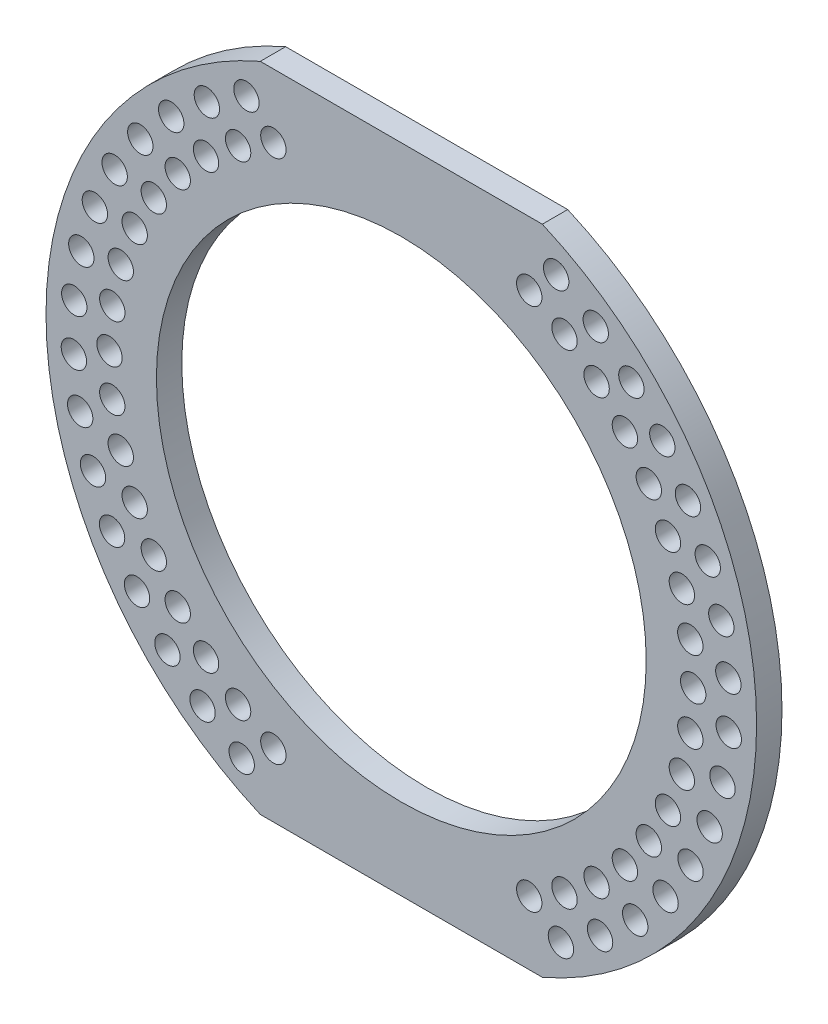
SolidWorks part; units mm, degrees
ref_plane "Ön Düzlem" through (0, 0, 0) normal (0, 0, 1) x (1, 0, 0)
ref_plane "Üst Düzlem" through (0, 0, 0) normal (0, 1, 0) x (1, 0, 0)
ref_plane "Sağ Düzlem" through (0, 0, 0) normal (1, 0, 0) x (0, 0, -1)
sketch "Çizim1" plane through (0, 0, 0) normal (0, 0, 1) x (1, 0, 0)
  line L1 (-11.1135, 25.7) -> (11.1135, 25.7)
  line L3 (-11.1135, -25.7) -> (11.1135, -25.7)
  arc A0 (-11.1135, 25.7) -> (-11.1135, -25.7) centre (0, 0) ccw
  arc A1 (11.1135, -25.7) -> (11.1135, 25.7) centre (0, 0) ccw
  dimension "D1" = 56
  dimension "D2" = 25.7
extrude "Yükseklik-Ekstrüzyon1" add sketch "Çizim1" along normal blind 2
sketch "Çizim2" plane through (0, 0, 2) normal (0, 0, 1) x (1, 0, 0)
  circle A0 centre (0, 0) radius 19.3
  dimension "D1" = 38.6
extrude "Kes-Ekstrüzyon1" cut sketch "Çizim2" against normal blind 3
sketch "Çizim3" plane through (0, 0, 2) normal (0, 0, 1) x (1, 0, 0)
  circle A0 centre (-23, 0) radius 1
  circle A3 centre (-22.7762, 3.201) radius 1
  circle A4 centre (-22.109, 6.3397) radius 1
  circle A5 centre (-21.0115, 9.3549) radius 1
  circle A6 centre (-19.5051, 12.1881) radius 1
  circle A7 centre (-17.619, 14.7841) radius 1
  circle A8 centre (-15.39, 17.0923) radius 1
  circle A9 centre (-12.8614, 19.0679) radius 1
  circle A10 centre (-10.0825, 20.6723) radius 1
  circle A39 centre (-10.0825, -20.6723) radius 1
  circle A40 centre (-12.8614, -19.0679) radius 1
  circle A41 centre (-15.39, -17.0923) radius 1
  circle A42 centre (-17.619, -14.7841) radius 1
  circle A43 centre (-19.5051, -12.1881) radius 1
  circle A44 centre (-21.0115, -9.3549) radius 1
  circle A45 centre (-22.109, -6.3397) radius 1
  circle A46 centre (-22.7762, -3.201) radius 1
  arc A47 (-8.0515, 21.5447) -> (-6.1498, 22.1626) centre (-7.1074, 21.8743) ccw [skipped]
  circle A48 centre (10.0825, -20.6723) radius 1
  arc A49 (-3.0056, 22.8028) -> (-4.9747, 22.4556) centre (-3.9939, 22.6506) ccw [skipped]
  circle A50 centre (12.8614, -19.0679) radius 1
  arc A51 (-1.8011, 22.9294) -> (0.1972, 22.9992) centre (-0.8027, 22.986) ccw [skipped]
  arc A52 (1.4076, 22.9569) -> (3.3962, 22.7479) centre (2.4042, 22.874) ccw [skipped]
  circle A53 centre (15.39, -17.0923) radius 1
  arc A54 (6.529, 22.0538) -> (4.5889, 22.5376) centre (5.5642, 22.3168) ccw [skipped]
  circle A55 centre (17.619, -14.7841) radius 1
  arc A56 (7.6808, 21.6796) -> (9.5348, 20.9306) centre (8.616, 21.3252) ccw [skipped]
  arc A57 (-8.0515, -21.5447) -> (-6.1498, -22.1626) centre (-7.1074, -21.8743) ccw [skipped]
  arc A58 (-3.0056, -22.8028) -> (-4.9747, -22.4556) centre (-3.9939, -22.6506) ccw [skipped]
  arc A59 (12.355, 19.3999) -> (10.6233, 20.3996) centre (11.5, 19.9186) ccw [skipped]
  circle A60 centre (19.5051, -12.1881) radius 1
  arc A61 (19.1774, 12.6975) -> (18.0022, 14.3151) centre (18.6074, 13.5191) ccw [skipped]
  arc A62 (13.359, 18.7226) -> (14.9347, 17.4916) centre (14.1602, 18.1242) ccw [skipped]
  arc A63 (17.2237, 15.2429) -> (15.8347, 16.6812) centre (16.5448, 15.9771) ccw [skipped]
  circle A64 centre (21.0115, -9.3549) radius 1
  arc A65 (20.758, 9.9049) -> (19.8192, 11.6704) centre (20.3078, 10.7978) ccw [skipped]
  arc A66 (21.2506, 8.7985) -> (21.9344, 6.9196) centre (21.6129, 7.8665) ccw [skipped]
  arc A67 (22.2683, 5.7554) -> (22.684, 3.7995) centre (22.4974, 4.782) ccw [skipped]
  arc A68 (22.992, -0.6056) -> (22.8525, -2.6002) centre (22.944, -1.6044) ccw [skipped]
  circle A69 centre (22.944, 1.6044) radius 1 [skipped]
  circle A70 centre (22.109, -6.3397) radius 1
  circle A71 centre (22.4974, -4.782) radius 1 [skipped]
  circle A72 centre (22.7762, -3.201) radius 1
  circle A73 centre (23, 0) radius 1
  arc A74 (15.8347, -16.6812) -> (17.2237, -15.2429) centre (16.5448, -15.9771) ccw [skipped]
  circle A75 centre (22.7762, 3.201) radius 1
  arc A76 (3.3962, -22.7479) -> (1.4076, -22.9569) centre (2.4042, -22.874) ccw [skipped]
  circle A77 centre (22.109, 6.3397) radius 1
  arc A78 (6.529, -22.0538) -> (4.5889, -22.5376) centre (5.5642, -22.3168) ccw [skipped]
  arc A79 (-1.8011, -22.9294) -> (0.1972, -22.9992) centre (-0.8027, -22.986) ccw [skipped]
  circle A80 centre (21.0115, 9.3549) radius 1
  arc A81 (9.5348, -20.9306) -> (7.6808, -21.6796) centre (8.616, -21.3252) ccw [skipped]
  arc A82 (10.6233, -20.3996) -> (12.355, -19.3999) centre (11.5, -19.9186) ccw [skipped]
  arc A83 (21.2506, -8.7985) -> (21.9344, -6.9196) centre (21.6129, -7.8665) ccw [skipped]
  arc A84 (19.1774, -12.6975) -> (18.0022, -14.3151) centre (18.6074, -13.5191) ccw [skipped]
  arc A85 (19.8192, -11.6704) -> (20.758, -9.9049) centre (20.3078, -10.7978) ccw [skipped]
  arc A86 (14.9347, -17.4916) -> (13.359, -18.7226) centre (14.1602, -18.1242) ccw [skipped]
  circle A87 centre (19.5051, 12.1881) radius 1
  circle A88 centre (17.619, 14.7841) radius 1
  circle A89 centre (15.39, 17.0923) radius 1
  circle A90 centre (12.8614, 19.0679) radius 1
  circle A91 centre (10.0825, 20.6723) radius 1
  point P96 (0, 0)
  dimension "D1" = 2
  dimension "D2" = 23
  dimension "D3" = 45
extrude "Kes-Ekstrüzyon2" cut sketch "Çizim3" against normal blind 3
sketch "Çizim4" plane through (0, 0, 2) normal (0, 0, 1) x (1, 0, 0)
  circle A1 centre (-12.2039, 22.7936) radius 1
  circle A30 centre (-12.5773, -22.5897) radius 1
  circle A31 centre (-15.6641, -20.5698) radius 1
  circle A32 centre (-18.4321, -18.1312) radius 1
  circle A33 centre (-20.8248, -15.3235) radius 1
  circle A34 centre (-22.7936, -12.2039) radius 1
  circle A35 centre (-24.2984, -8.8358) radius 1
  circle A36 centre (-25.3085, -5.2878) radius 1
  circle A37 centre (-25.8034, -1.6322) radius 1
  circle A38 centre (-25.7731, 2.0566) radius 1
  circle A39 centre (-25.2181, 5.7036) radius 1
  circle A40 centre (-24.1497, 9.2344) radius 1
  circle A41 centre (-22.5897, 12.5773) radius 1
  circle A42 centre (-20.5698, 15.6641) radius 1
  circle A43 centre (-18.1312, 18.4321) radius 1
  circle A44 centre (-15.3235, 20.8248) radius 1
  circle A45 centre (12.5773, -22.5897) radius 1
  arc A46 (-9.7688, 23.9385) -> (-7.8895, 24.6219) centre (-8.8358, 24.2984) ccw [skipped]
  arc A47 (-10.1614, -23.7745) -> (-8.2936, -24.4887) centre (-9.2344, -24.1497) ccw [skipped]
  arc A48 (-6.6745, -24.9786) -> (-4.7241, -25.4198) centre (-5.7036, -25.2181) ccw [skipped]
  circle A49 centre (15.6641, -20.5698) radius 1
  arc A50 (2.6288, -25.721) -> (0.6332, -25.8473) centre (1.6322, -25.8034) ccw [skipped]
  circle A51 centre (18.4321, -18.1312) radius 1
  arc A52 (6.2625, -25.0851) -> (4.3052, -25.4941) centre (5.2878, -25.3085) ccw [skipped]
  arc A53 (-1.0584, -25.8333) -> (-3.0517, -25.6743) centre (-2.0566, -25.7731) ccw [skipped]
  arc A54 (7.8895, -24.6219) -> (9.7688, -23.9385) centre (8.8358, -24.2984) ccw [skipped]
  circle A55 centre (20.8248, -15.3235) radius 1
  arc A56 (23.0591, -11.6943) -> (22.0864, -13.4414) centre (22.5897, -12.5773) ccw [skipped]
  circle A57 centre (22.7936, -12.2039) radius 1
  arc A58 (11.3133, -23.2485) -> (13.0762, -22.3046) centre (12.2039, -22.7936) ccw [skipped]
  circle A59 centre (18.1312, -18.4321) radius 1 [skipped]
  circle A60 centre (24.2984, -8.8358) radius 1
  arc A61 (16.1173, -20.2167) -> (14.5067, -21.4018) centre (15.3235, -20.8248) ccw [skipped]
  circle A62 centre (25.3085, -5.2878) radius 1
  arc A63 (21.1602, -14.857) -> (19.9487, -16.4478) centre (20.5698, -15.6641) ccw [skipped]
  circle A64 centre (25.8034, -1.6322) radius 1
  arc A65 (25.0851, 6.2625) -> (25.4941, 4.3052) centre (25.3085, 5.2878) ccw [skipped]
  arc A66 (25.6743, -3.0517) -> (25.8333, -1.0584) centre (25.7731, -2.0566) ccw [skipped]
  arc A67 (24.9786, -6.6745) -> (25.4198, -4.7241) centre (25.2181, -5.7036) ccw [skipped]
  arc A68 (24.4887, -8.2936) -> (23.7745, -10.1614) centre (24.1497, -9.2344) ccw [skipped]
  arc A69 (25.721, 2.6288) -> (25.8473, 0.6332) centre (25.8034, 1.6322) ccw [skipped]
  arc A70 (24.6219, 7.8895) -> (23.9385, 9.7688) centre (24.2984, 8.8358) ccw [skipped]
  circle A71 centre (25.7731, 2.0566) radius 1
  arc A72 (20.2167, 16.1173) -> (21.4018, 14.5067) centre (20.8248, 15.3235) ccw [skipped]
  circle A73 centre (25.2181, 5.7036) radius 1
  arc A74 (-6.2625, 25.0851) -> (-4.3052, 25.4941) centre (-5.2878, 25.3085) ccw [skipped]
  circle A75 centre (24.1497, 9.2344) radius 1
  arc A76 (-2.6288, 25.721) -> (-0.6332, 25.8473) centre (-1.6322, 25.8034) ccw [skipped]
  arc A77 (1.0584, 25.8333) -> (3.0517, 25.6743) centre (2.0566, 25.7731) ccw [skipped]
  circle A78 centre (22.5897, 12.5773) radius 1
  circle A79 centre (20.5698, 15.6641) radius 1
  arc A80 (13.4414, 22.0864) -> (11.6943, 23.0591) centre (12.5773, 22.5897) ccw [skipped]
  arc A81 (8.2936, 24.4887) -> (10.1614, 23.7745) centre (9.2344, 24.1497) ccw [skipped]
  arc A82 (4.7241, 25.4198) -> (6.6745, 24.9786) centre (5.7036, 25.2181) ccw [skipped]
  circle A83 centre (18.1312, 18.4321) radius 1
  arc A84 (19.1194, 17.4049) -> (17.7171, 18.8304) centre (18.4321, 18.1312) ccw [skipped]
  arc A85 (14.857, 21.1602) -> (16.4478, 19.9487) centre (15.6641, 20.5698) ccw [skipped]
  arc A86 (23.2485, 11.3133) -> (22.3046, 13.0762) centre (22.7936, 12.2039) ccw [skipped]
  circle A87 centre (15.3235, 20.8248) radius 1
  circle A88 centre (12.2039, 22.7936) radius 1
  point P96 (0, 0)
  dimension "D2" = 2
  dimension "D3" = 44
extrude "Kes-Ekstrüzyon3" cut sketch "Çizim4" against normal blind 3
